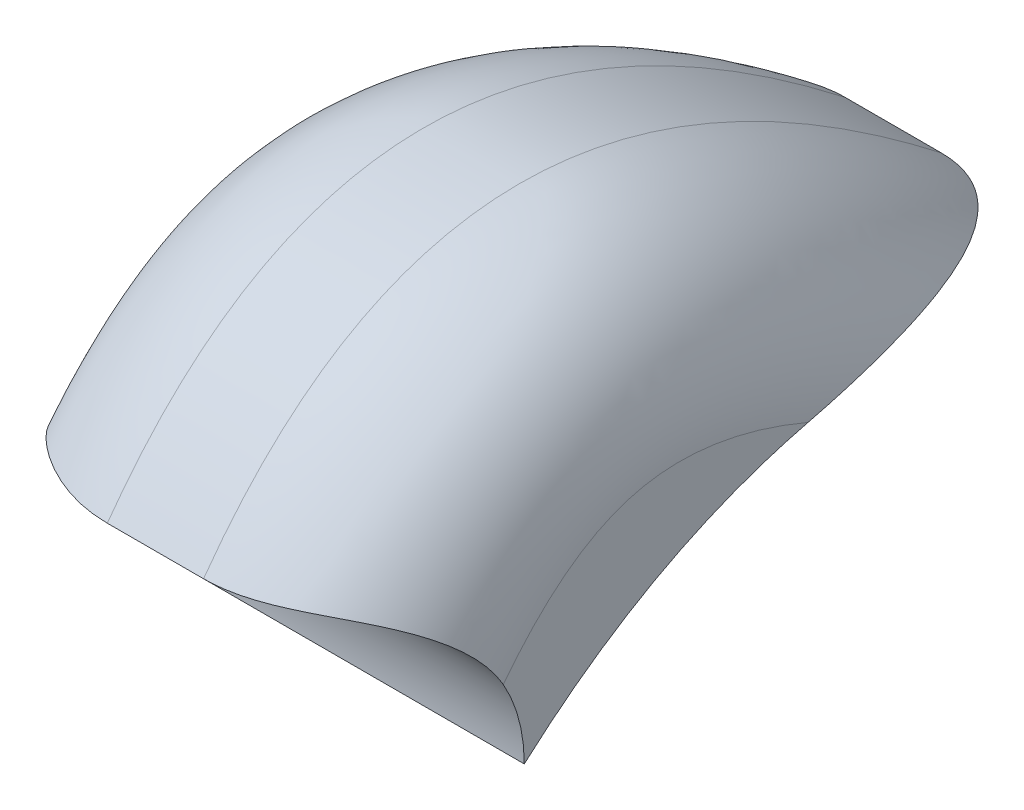
SolidWorks part; units mm, degrees
ref_plane "Front Plane" through (0, 0, 0) normal (0, 0, 1) x (1, 0, 0)
ref_plane "Top Plane" through (0, 0, 0) normal (0, 1, 0) x (1, 0, 0)
ref_plane "Right Plane" through (0, 0, 0) normal (1, 0, 0) x (0, 0, -1)
sketch "Sketch1" plane through (0, 0, 0) normal (1, 0, 0) x (0, 0, -1)
  arc A0 (12.7, 0) -> (0, 12.7) centre (0, 0) ccw
  spline S0 degree 2 poles (0, 12.7) (20.8644, 41.8846) (58.42, 12.7) knots 0 0 0 1 1 1
  spline S1 degree 2 poles (12.7, 0) (31.8912, 17.2712) (58.42, 12.7) knots 0 0 0 1 1 1
  dimension "D1" = 25.4
extrude "Boss-Extrude1" add sketch "Sketch1" along normal blind 33.02
fillet "Fillet1" radius 12.7 2 edges
shell "Shell1" thickness 0.508
